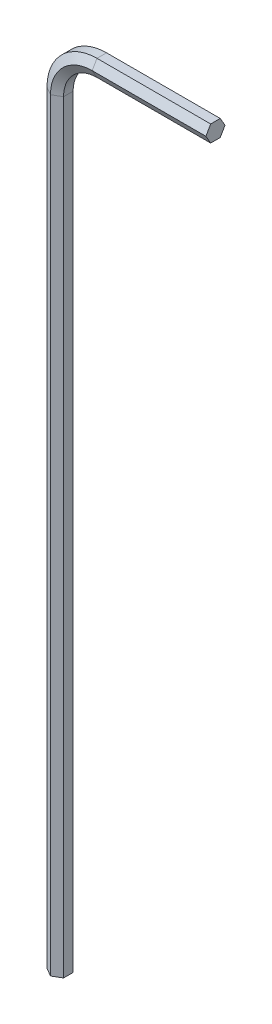
SolidWorks part; units mm, degrees
other "Defeature"
material "Plain Carbon Steel"
ref_plane "Front Plane" through (0, 0, 0) normal (0, 0, 1) x (1, 0, 0)
ref_plane "Top Plane" through (0, 0, 0) normal (0, 1, 0) x (1, 0, 0)
ref_plane "Right Plane" through (0, 0, 0) normal (1, 0, 0) x (0, 0, -1)
sketch "Sketch1" plane through (0, 0, 0) normal (0, 0, 1) x (1, 0, 0)
  line L0 (0, 0) -> (0, 73.2062)
  line L1 (4, 77.2062) -> (14.9062, 77.2062)
  arc A0 (0, 73.2062) -> (4, 77.2062) centre (4, 73.2062) cw
  point P6 (0, 77.2062)
  dimension "D1" = 4
  dimension "D2" = 77.2062
  dimension "D3" = 14.9062
sketch "Sketch2" plane through (0, 0, 0) normal (0, 1, 0) x (1, 0, 0)
  line L1 (0, 0.9165) -> (-0.7937, 0.4583)
  line L2 (-0.7937, 0.4583) -> (-0.7937, -0.4583)
  line L3 (-0.7937, -0.4583) -> (0, -0.9165)
  line L4 (0, -0.9165) -> (0.7938, -0.4583)
  line L5 (0.7938, -0.4583) -> (0.7937, 0.4583)
  line L6 (0.7937, 0.4583) -> (0, 0.9165)
  circle A0 centre (0, 0) radius 0.7938 construction
  dimension "D1" = 1.5875
sweep "Sweep1" add profiles "Sketch2" path "Sketch1"
